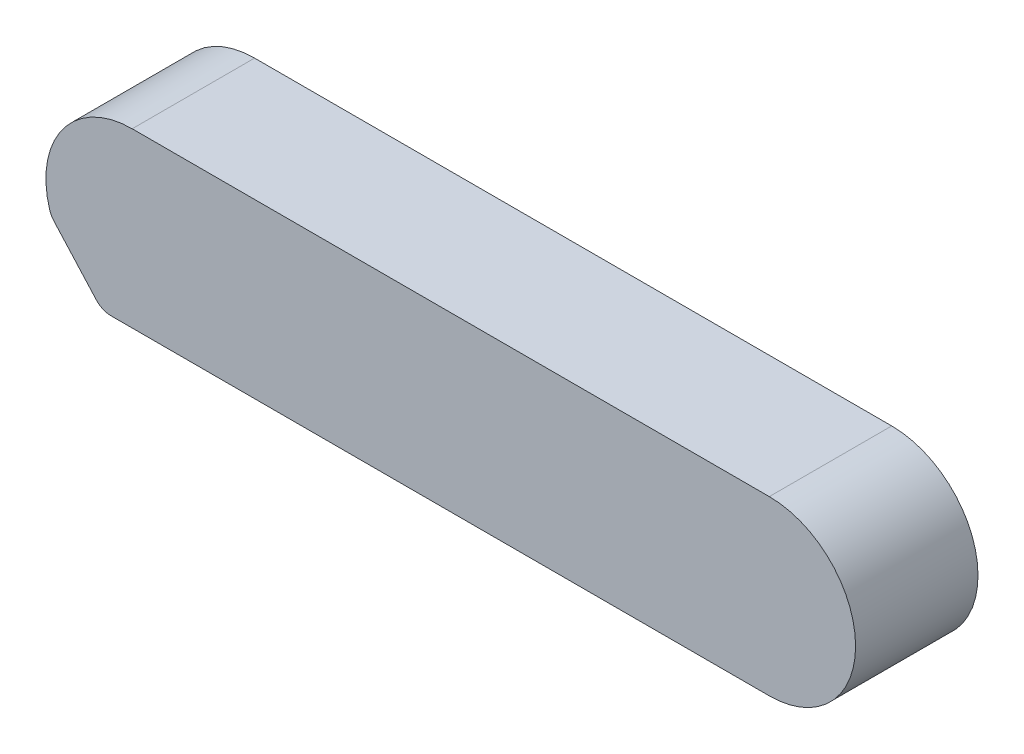
SolidWorks part; units mm, degrees
ref_plane "Plan de face" through (0, 0, 0) normal (0, 0, 1) x (1, 0, 0)
ref_plane "Plan de dessus" through (0, 0, 0) normal (0, 1, 0) x (1, 0, 0)
ref_plane "Plan de droite" through (0, 0, 0) normal (1, 0, 0) x (0, 0, -1)
sketch "Esquisse1" plane through (0, 0, 0) normal (0, 0, 1) x (1, 0, 0)
  line L0 (-356.4814, -16.3659) -> (-335.4792, -39.6913)
  line L1 (0, -43) -> (-328.0477, -43)
  line L3 (0, 43) -> (-317.5, 43)
  arc A0 (0, 43) -> (0, -43) centre (0, 0) cw
  arc A1 (-317.5, 43) -> (-358.6106, -12.6063) centre (-317.5, 0) ccw
  arc A2 (-328.0477, -43) -> (-335.4792, -39.6913) centre (-328.0477, -33) cw
  arc A3 (-356.4814, -16.3659) -> (-358.6106, -12.6063) centre (-349.05, -9.6746) cw
  point P10 (-332.5, -43)
  dimension "D1" = 43
  dimension "D4" = 15
  dimension "D5" = 10
  dimension "D2" = 317.5
  dimension "D3" = 48
extrude "Extrusion1" add sketch "Esquisse1" along normal blind 60 and the other way blind 1
